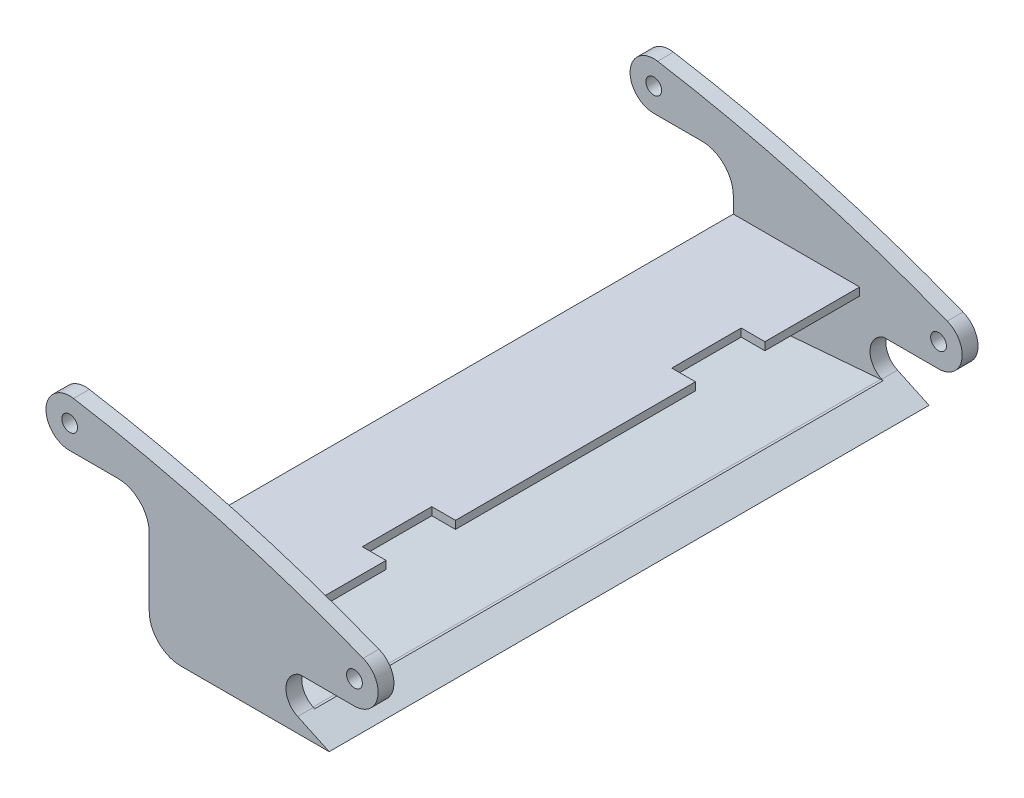
SolidWorks part; units mm, degrees
ref_plane "Front Plane" through (0, 0, 0) normal (0, 0, 1) x (1, 0, 0)
ref_plane "Top Plane" through (0, 0, 0) normal (0, 1, 0) x (1, 0, 0)
ref_plane "Right Plane" through (0, 0, 0) normal (1, 0, 0) x (0, 0, -1)
sketch "Sketch1" plane through (0, 0, 0) normal (0, 0, 1) x (1, 0, 0)
  line L0 (0, 0) -> (47, 0)
  line L1 (47, 0) -> (37, 4.6631)
  line L3 (-10, 10) -> (-10, 31.5017)
  line L4 (47, 0) -> (55, 0) construction
  line L7 (55, 0) -> (55, 24.0017) construction
  line L8 (55, 16.5017) -> (37.5848, 16.5017)
  line L11 (-20, 41.5017) -> (-35.1979, 41.5017)
  circle A1 centre (55, 24.0017) radius 2.5
  arc A2 (55, 16.5017) -> (57.7564, 30.9769) centre (55, 24.0017) ccw
  arc A3 (37, 4.6631) -> (37.5848, 16.5017) centre (39.7047, 10.4633) cw
  circle A4 centre (-35.1979, 49.0017) radius 2.5
  arc A5 (-33.9703, 56.4006) -> (-35.1979, 41.5017) centre (-35.1979, 49.0017) ccw
  arc A6 (-20, 41.5017) -> (-10, 31.5017) centre (-20, 31.5017) cw
  arc A7 (-10, 10) -> (0, 0) centre (0, 10) ccw
  arc A8 (-33.9703, 56.4006) -> (57.7564, 30.9769) centre (-107.6272, -387.5303) cw
  dimension "D4" = 450
  dimension "D9" = 47
  dimension "D10" = 21.5017
  dimension "D11" = 10
  dimension "D13" = 5
  dimension "D14" = 5
  dimension "D6" = 25
  dimension "D7" = 6.3998
  dimension "D15" = 35.1979
  dimension "D3" = 10
  dimension "D5" = 7.5
  dimension "D12" = 7.5
  dimension "D1" = 10
  dimension "D2" = 8
  dimension "D8" = 17.4152
extrude "Boss-Extrude1" add sketch "Sketch1" along normal blind 190
ref_plane "Plane1" through (0, 62.4697, 0) normal (0, 1, 0) x (1, 0, 0)
sketch "Sketch2" plane through (0, 62.4697, 0) normal (0, 1, 0) x (1, 0, 0)
  line L0 (57.7564, 0) -> (-33.9703, 0) construction
  line L1 (-56.3606, -5) -> (79.7669, -5)
  line L2 (-56.3606, -5) -> (-56.3606, -185)
  line L3 (-56.3606, -185) -> (79.7669, -185)
  line L4 (79.7669, -5) -> (79.7669, -185)
  line L5 (-33.9703, -190) -> (57.7564, -190) construction
  dimension "D1" = 5
  dimension "D2" = 5
extrude "Cut-Extrude2" cut sketch "Sketch2" against normal blind 58
sketch "Sketch3" plane through (0, 4.4697, 0) normal (0, 1, 0) x (1, 0, 0)
  line L1 (36.6684, -5) -> (-8.3316, -5)
  line L2 (36.6684, -5) -> (36.6684, -185)
  line L3 (36.6684, -185) -> (-8.3316, -185)
  line L4 (-8.3316, -5) -> (-8.3316, -185)
  dimension "D1" = 45
  dimension "D2" = 180
extrude "Cut-Extrude3" cut sketch "Sketch3" against normal blind 3
sketch "Sketch4" plane through (0, 0, 185) normal (0, 0, -1) x (-1, 0, 0)
  line L0 (-30, 26.4697) -> (-30, 1.4697)
  line L1 (-30, 26.4697) -> (10, 26.4697)
  line L2 (10, 10) -> (10, 31.5017) construction
  line L3 (10, 26.4697) -> (10, 10)
  line L4 (5.2186, 1.4697) -> (-30, 1.4697)
  line L5 (5.2186, 1.4697) -> (-36.6684, 1.4697) construction
  line L6 (-27.5, 23.9697) -> (7.5, 23.9697)
  line L7 (7.5, 23.9697) -> (7.5, 10)
  line L8 (4.4593, 3.9697) -> (-27.5, 3.9697)
  line L9 (-27.5, 23.9697) -> (-27.5, 3.9697)
  arc A1 (10, 10) -> (5.2186, 1.4697) centre (0, 10) cw
  arc A3 (7.5, 10) -> (4.4593, 3.9697) centre (0, 10) cw
  dimension "D1" = 40
  dimension "D2" = 25
  dimension "D3" = 2.5
extrude "Boss-Extrude2" add sketch "Sketch4" along normal blind 180
sketch "Sketch7" plane through (30, 0, 0) normal (1, 0, 0) x (0, 0, -1)
  line L18 (-5, 26.4697) -> (-185, 26.4697) construction
  line L19 (-185, 1.4697) -> (-5, 1.4697)
  line L20 (-185, 1.4697) -> (-185, 23.9697)
  line L21 (-185, 23.9697) -> (-5, 23.9697)
  line L22 (-5, 1.4697) -> (-5, 23.9697)
  dimension "D1" = 180
  dimension "D2" = 2.5
extrude "Cut-Extrude13" cut sketch "Sketch7" against normal blind 30
ref_plane "Plane2" through (0, 0, 95) normal (0, 0, 1) x (1, 0, 0)
sketch "Sketch9" plane through (0, 26.4697, 0) normal (0, 1, 0) x (1, 0, 0)
  line L0 (30, -5) -> (30, -185) construction
  line L1 (30, -57) -> (22.5, -57)
  line L2 (30, -57) -> (30, -35)
  line L3 (30, -35) -> (22.5, -35)
  line L4 (22.5, -57) -> (22.5, -35)
  line L5 (-33.9703, -5) -> (57.7564, -5) construction
  dimension "D1" = 7.5
  dimension "D2" = 22
  dimension "D3" = 30
extrude "Cut-Extrude14" cut sketch "Sketch9" against normal blind 3
mirror "Mirror1" about plane through (0, 0, 95) normal (0, 0, 1) of "Cut-Extrude14"
sketch "Sketch10" plane through (0, 0, 185) normal (0, 0, -1) x (-1, 0, 0)
  line L0 (-36.6684, 1.4697) -> (-36.6684, 4.4697)
  line L1 (-36.6684, 4.4697) -> (0, 1.4697)
  line L2 (0, 1.4697) -> (-36.6684, 1.4697)
extrude "Boss-Extrude3" add sketch "Sketch10" along normal up to surface (180 mm away) up to face at (-37.6979, 49.0017, 5)
